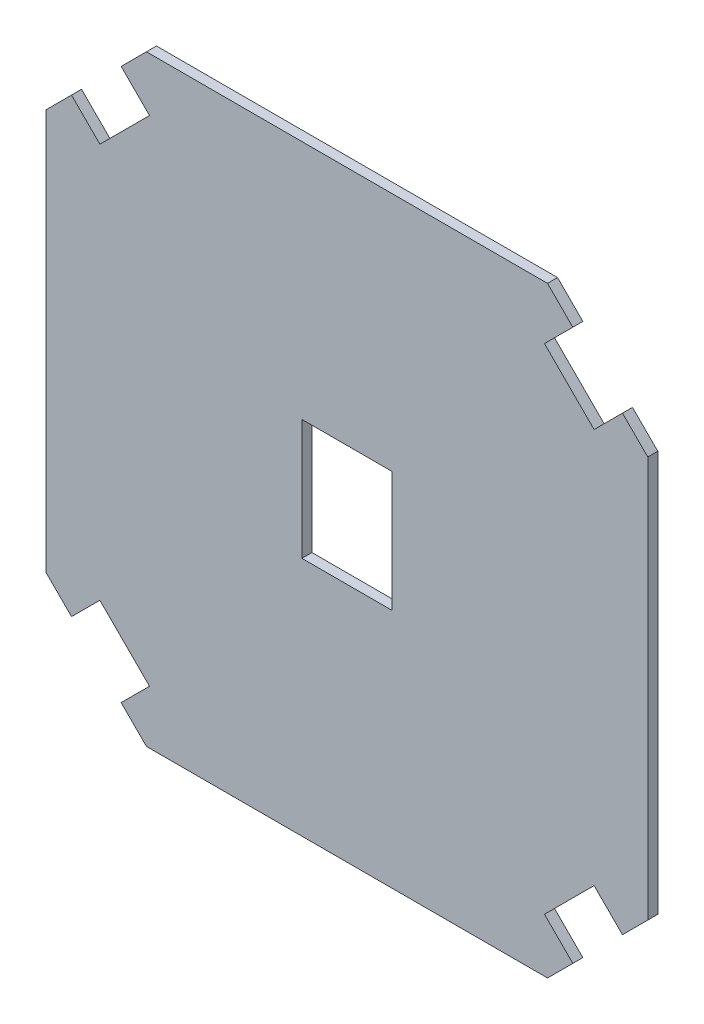
SolidWorks part; units mm, degrees
ref_plane "Plan de face" through (0, 0, 0) normal (0, 0, 1) x (1, 0, 0)
ref_plane "Plan de dessus" through (0, 0, 0) normal (0, 1, 0) x (1, 0, 0)
ref_plane "Plan de droite" through (0, 0, 0) normal (1, 0, 0) x (0, 0, -1)
sketch "Esquisse1" plane through (0, 0, 0) normal (0, 0, 1) x (1, 0, 0)
  line L0 (100, 150) -> (150, 100)
  line L1 (150, -150) -> (-150, -150)
  line L2 (150, -150) -> (150, 150)
  line L3 (150, 150) -> (-150, 150)
  line L4 (-150, -150) -> (-150, 150)
  line L5 (150, -150) -> (-150, 150) construction
  line L6 (150, 150) -> (-150, -150) construction
  line L7 (0, 237.159) -> (0, -197.6632) construction
  line L8 (-230.3021, 0) -> (257.9193, 0) construction
  line L9 (-100, 150) -> (-150, 100)
  line L10 (100, -150) -> (150, -100)
  line L11 (-100, -150) -> (-150, -100)
  line L18 (22.5, -30) -> (-22.5, -30)
  line L22 (-137.3744, 112.6256) -> (-123.2322, 98.4835)
  line L23 (-123.2322, 98.4835) -> (-98.4835, 123.2322)
  line L24 (-98.4835, 123.2322) -> (-112.6256, 137.3744)
  line L25 (137.3744, 112.6256) -> (123.2322, 98.4835)
  line L26 (123.2322, 98.4835) -> (98.4835, 123.2322)
  line L27 (98.4835, 123.2322) -> (112.6256, 137.3744)
  line L28 (-137.3744, -112.6256) -> (-123.2322, -98.4835)
  line L29 (-123.2322, -98.4835) -> (-98.4835, -123.2322)
  line L30 (-98.4835, -123.2322) -> (-112.6256, -137.3744)
  line L31 (137.3744, -112.6256) -> (123.2322, -98.4835)
  line L32 (98.4835, -123.2322) -> (112.6256, -137.3744)
  line L33 (123.2322, -98.4835) -> (98.4835, -123.2322)
  line L34 (22.5, -30) -> (22.5, 30)
  line L35 (22.5, 30) -> (-22.5, 30)
  line L36 (-22.5, -30) -> (-22.5, 30)
  line L37 (22.5, -30) -> (-22.5, 30) construction
  line L38 (22.5, 30) -> (-22.5, -30) construction
  point P0 (0, 0)
  point P18 (-90, 0)
  point P19 (0, 0)
  point P31 (-110.8579, 110.8579)
  dimension "D1" = 300
  dimension "D2" = 300
  dimension "D3" = 45
  dimension "D4" = 50
  dimension "D5" = 60
  dimension "D6" = 45
  dimension "D8" = 35
  dimension "D9" = 20
extrude "Boss.-Extru.1" add sketch "Esquisse1" along normal blind 5
